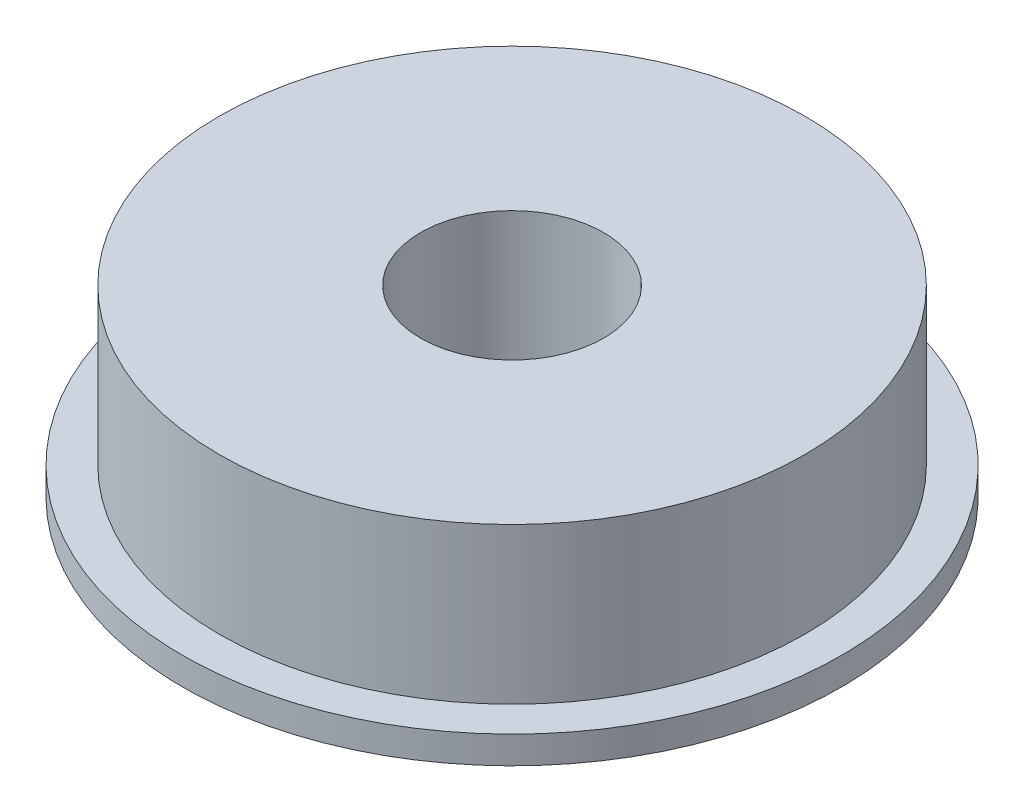
SolidWorks part; units mm, degrees
ref_plane "Front Plane" through (0, 0, 0) normal (0, 0, 1) x (1, 0, 0)
ref_plane "Top Plane" through (0, 0, 0) normal (0, 1, 0) x (1, 0, 0)
ref_plane "Right Plane" through (0, 0, 0) normal (1, 0, 0) x (0, 0, -1)
sketch "Sketch1" plane through (0, 0, 0) normal (1, 0, 0) x (0, 0, -1)
  line L0 (0, 0) -> (0, 5)
  line L1 (0, 5) -> (8, 5)
  line L2 (8, 5) -> (8, 0.75)
  line L3 (8, 0.75) -> (9, 0.75)
  line L4 (9, 0.75) -> (9, 0)
  line L5 (9, 0) -> (0, 0)
  dimension "D1" = 8
  dimension "9" = 9
  dimension "D3" = 5
  dimension "D4" = 0.75
revolve "Revolve1" add sketch "Sketch1" angle 360 about L0
sketch "Sketch2" plane through (0, 5, 0) normal (0, 1, 0) x (1, 0, 0)
  circle A0 centre (0, 0) radius 2.5
  dimension "D1" = 5
extrude "Cut-Extrude1" cut sketch "Sketch2" against normal through all
